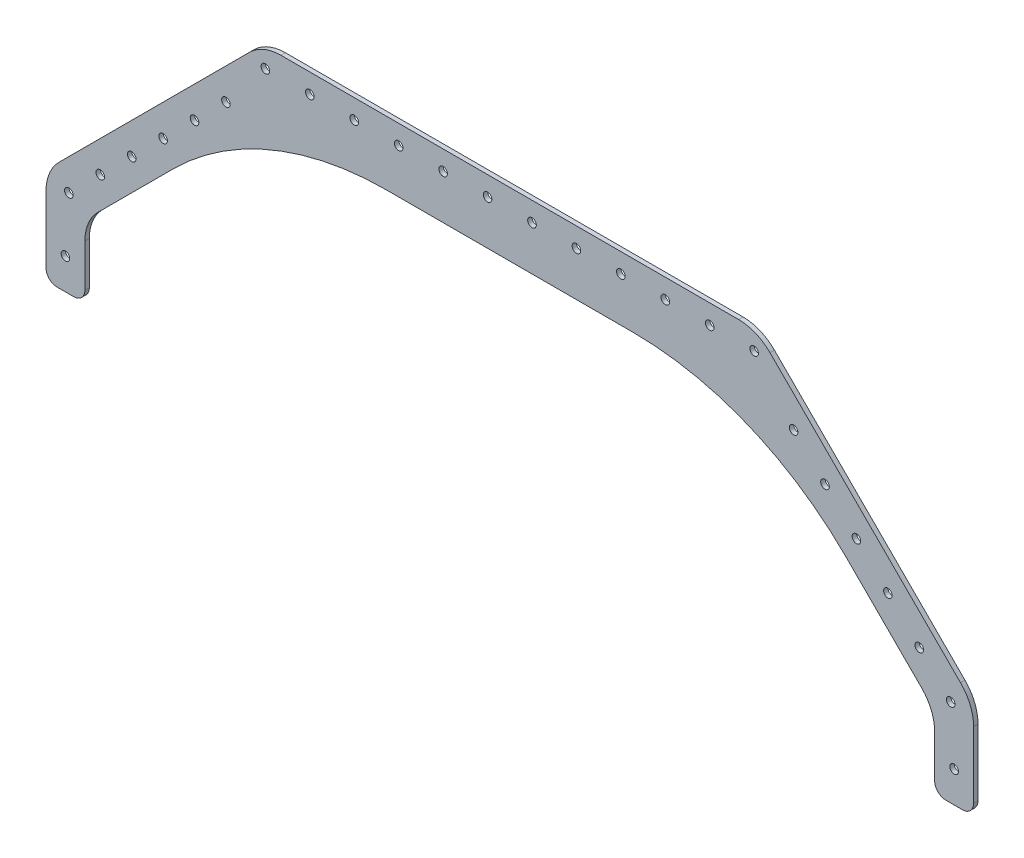
SolidWorks part; units mm, degrees
ref_plane "Front" through (0, 0, 0) normal (0, 0, 1) x (1, 0, 0)
ref_plane "Top" through (0, 0, 0) normal (0, 1, 0) x (1, 0, 0)
ref_plane "Right" through (0, 0, 0) normal (1, 0, 0) x (0, 0, -1)
sketch "Sketch1" plane through (0, 0, 0) normal (0, 0, 1) x (1, 0, 0)
  line L0 (266.7, 88.6025) -> (129.179, 226.1235) construction
  line L1 (258.7625, 71.1962) -> (249.2375, 71.1962)
  line L2 (265.1125, 77.5462) -> (265.1125, 115.59)
  line L3 (130.7665, 249.936) -> (-130.7665, 249.936)
  line L4 (-265.1125, 77.5462) -> (-265.1125, 115.59)
  line L5 (-266.7, 124.5235) -> (-165.1, 226.1235) construction
  line L7 (192.3832, 162.9192) -> (235.448, 119.8545)
  line L8 (-148.727, 242.4965) -> (-257.673, 133.5505)
  line L9 (257.673, 133.5505) -> (148.727, 242.4965)
  line L10 (242.8875, 77.5462) -> (242.8875, 101.894)
  line L11 (-242.8875, 101.894) -> (-242.8875, 77.5462)
  line L12 (70.4552, 213.4235) -> (-70.4552, 213.4235)
  line L13 (253.9238, 69.6087) -> (241.3, 69.6087) construction
  line L15 (241.3, 6.35) -> (241.3, 114.0025) construction
  line L20 (266.7, 6.35) -> (266.7, 88.6025) construction
  line L22 (-249.2375, 71.1962) -> (-258.7625, 71.1962)
  line L23 (266.7, 124.5235) -> (165.1, 226.1235) construction
  line L25 (165.1, 226.1235) -> (-165.1, 226.1235) construction
  line L26 (139.7, 251.5235) -> (-139.7, 251.5235) construction
  line L27 (-235.448, 119.8545) -> (-192.3832, 162.9192)
  line L28 (-266.7, 88.6025) -> (-129.179, 226.1235) construction
  arc A0 (192.3832, 162.9192) -> (70.4552, 213.4235) centre (70.4552, 40.9912) ccw
  arc A1 (-70.4552, 213.4235) -> (-192.3832, 162.9192) centre (-70.4552, 40.9912) ccw
  arc A2 (242.8875, 101.894) -> (235.448, 119.8545) centre (217.4875, 101.894) ccw
  arc A3 (-235.448, 119.8545) -> (-242.8875, 101.894) centre (-217.4875, 101.894) ccw
  arc A4 (-257.673, 133.5505) -> (-265.1125, 115.59) centre (-239.7125, 115.59) ccw
  arc A5 (257.673, 133.5505) -> (265.1125, 115.59) centre (239.7125, 115.59) cw
  arc A6 (148.727, 242.4965) -> (130.7665, 249.936) centre (130.7665, 224.536) ccw
  arc A7 (258.7625, 71.1962) -> (265.1125, 77.5462) centre (258.7625, 77.5462) ccw
  arc A8 (242.8875, 77.5462) -> (249.2375, 71.1962) centre (249.2375, 77.5462) ccw
  arc A9 (-242.8875, 77.5462) -> (-249.2375, 71.1962) centre (-249.2375, 77.5462) cw
  arc A10 (-258.7625, 71.1962) -> (-265.1125, 77.5462) centre (-258.7625, 77.5462) cw
  arc A11 (-148.727, 242.4965) -> (-130.7665, 249.936) centre (-130.7665, 224.536) cw
  point P0 (0, 0)
  dimension "D2" = 1.5875
  dimension "D1" = 12.7
  dimension "D3" = 25.4
  dimension "D7" = 25.4
  dimension "D8" = 6.35
  dimension "D4" = 1.5875
  dimension "D5" = 1.5875
  dimension "D6" = 1.5875
extrude "Boss-Extrude1" add sketch "Sketch1" along normal blind 2.54
hole_wizard "#8 Clearance Hole1" positions "Sketch2" profile "Sketch3" hole size "#8" standard "ANSI Inch" end condition through all
sketch "Sketch2" plane through (0, 0, 0) normal (0, 0, -1) x (-1, 0, 0)
  arc A0 (-254.0762, 91.0322) -> (-254.0762, 86.8948) centre (-254, 88.9635) ccw construction
  arc A1 (-250.6353, 122.7355) -> (-253.5609, 119.8099) centre (-252.0442, 121.2188) ccw construction
  arc A2 (-232.6748, 140.696) -> (-235.6003, 137.7704) centre (-234.0837, 139.1793) ccw construction
  arc A3 (217.6398, 155.7309) -> (214.7143, 158.6565) centre (216.1232, 157.1398) ccw construction
  arc A4 (253.9238, 91.0322) -> (253.9238, 86.8948) centre (254, 88.9635) ccw construction
  arc A5 (250.5275, 122.6277) -> (253.4531, 119.7021) centre (252.0442, 121.2188) ccw construction
  arc A6 (232.567, 140.5882) -> (235.4926, 137.6626) centre (234.0837, 139.1793) ccw construction
  arc A7 (196.646, 176.5092) -> (199.5716, 173.5837) centre (198.1626, 175.1003) ccw construction
  arc A9 (178.6855, 194.4698) -> (181.611, 191.5442) centre (180.2021, 193.0609) ccw construction
  arc A10 (160.725, 212.4303) -> (163.6505, 209.5047) centre (162.2416, 211.0214) ccw construction
  arc A11 (141.7687, 238.8997) -> (137.6313, 238.8997) centre (139.7, 238.8235) ccw construction
  arc A12 (116.3687, 238.8997) -> (112.2313, 238.8997) centre (114.3, 238.8235) ccw construction
  arc A13 (90.9687, 238.8997) -> (86.8313, 238.8997) centre (88.9, 238.8235) ccw construction
  arc A14 (65.5687, 238.8997) -> (61.4313, 238.8997) centre (63.5, 238.8235) ccw construction
  arc A15 (40.1687, 238.8997) -> (36.0313, 238.8997) centre (38.1, 238.8235) ccw construction
  circle A16 centre (12.7, 238.8235) radius 2.0701 construction
  arc A17 (-10.6313, 238.8997) -> (-14.7687, 238.8997) centre (-12.7, 238.8235) ccw construction
  arc A18 (-36.0313, 238.8997) -> (-40.1687, 238.8997) centre (-38.1, 238.8235) ccw construction
  arc A19 (-61.4313, 238.8997) -> (-65.5687, 238.8997) centre (-63.5, 238.8235) ccw construction
  arc A20 (-86.8313, 238.8997) -> (-90.9687, 238.8997) centre (-88.9, 238.8235) ccw construction
  arc A21 (-112.2313, 238.8997) -> (-116.3687, 238.8997) centre (-114.3, 238.8235) ccw construction
  arc A22 (-137.6313, 238.8997) -> (-141.7687, 238.8997) centre (-139.7, 238.8235) ccw construction
  arc A23 (-178.7932, 194.5775) -> (-181.7188, 191.6519) centre (-180.2021, 193.0609) ccw construction
  arc A24 (-196.7537, 176.617) -> (-199.6793, 173.6914) centre (-198.1626, 175.1003) ccw construction
  arc A25 (-214.7143, 158.6565) -> (-217.6398, 155.7309) centre (-216.1232, 157.1398) ccw construction
  point P6 (-254, 88.9635)
  point P19 (-252.0442, 121.2188)
  point P21 (-234.0837, 139.1793)
  point P24 (-216.1232, 157.1398)
  point P27 (-198.1626, 175.1003)
  point P30 (-180.2021, 193.0609)
  point P36 (-114.3, 238.8235)
  point P39 (-88.9, 238.8235)
  point P42 (-63.5, 238.8235)
  point P45 (-38.1, 238.8235)
  point P48 (-12.7, 238.8235)
  point P51 (12.7, 238.8235)
  point P54 (38.1, 238.8235)
  point P57 (63.5, 238.8235)
  point P60 (88.9, 238.8235)
  point P63 (114.3, 238.8235)
  point P66 (139.7, 238.8235)
  point P69 (162.2416, 211.0214)
  point P72 (180.2021, 193.0609)
  point P75 (198.1626, 175.1003)
  point P78 (216.1232, 157.1398)
  point P81 (234.0837, 139.1793)
  point P84 (252.0442, 121.2188)
  point P87 (254, 88.9635)
  point P99 (-139.7, 238.8235)
  point P232 (-162.2416, 211.0214)
  point P236 (0, 0)
  point P240 (0, 0)
  point P244 (0, 0)
sketch "Sketch3" plane through (254, 88.9635, 0) normal (1, 0, 0) x (0, 1, 0)
  line L0 (0, 0) -> (0, 2.54)
  line L1 (0, 2.54) -> (2.4574, 2.54)
  line L2 (2.4574, 2.54) -> (2.4574, 0)
  line L5 (2.4574, 0) -> (0, 0)
  line L11 (0, -6.35) -> (0, 107.95) construction
  dimension "Thru Hole Dia." = 4.9149
  dimension "Thru Hole Depth" = 2.54
